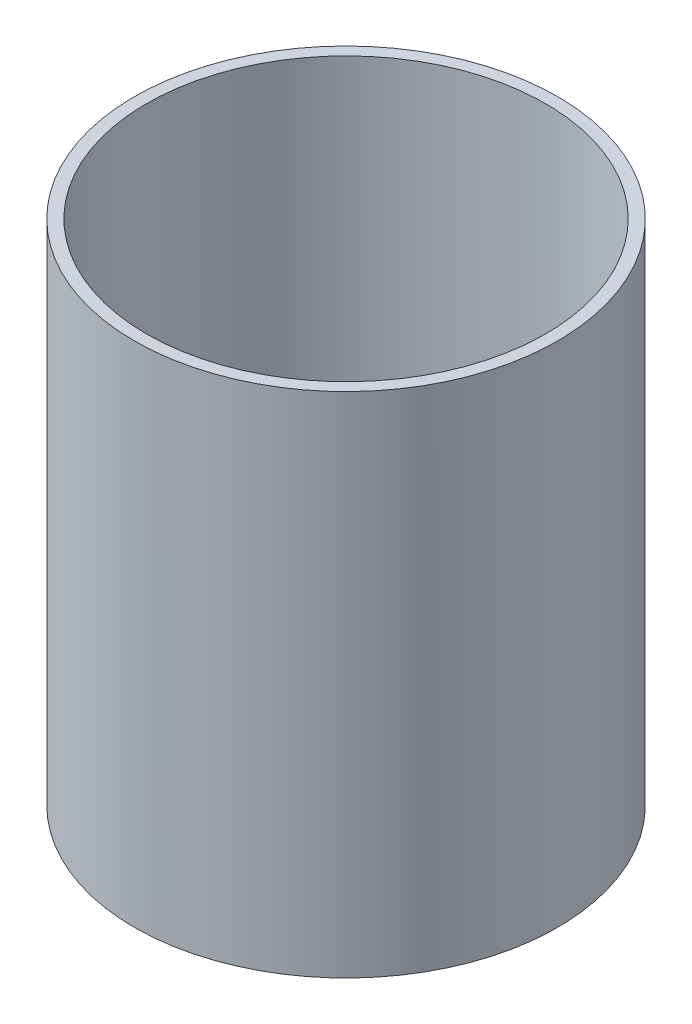
SolidWorks part; units mm, degrees
ref_plane "Front Plane" through (0, 0, 0) normal (0, 0, 1) x (1, 0, 0)
ref_plane "Top Plane" through (0, 0, 0) normal (0, 1, 0) x (1, 0, 0)
ref_plane "Right Plane" through (0, 0, 0) normal (1, 0, 0) x (0, 0, -1)
sketch "Sketch1" plane through (0, 0, 0) normal (0, 1, 0) x (1, 0, 0)
  circle A0 centre (0, 0) radius 17.78
  dimension "D1" = 35.56
extrude "Boss-Extrude1" add sketch "Sketch1" along normal blind 50.8 contours A0
sketch "Sketch2" plane through (0, 50.8, 0) normal (0, 1, 0) x (1, 0, 0)
  circle A0 centre (0, 0) radius 16.764
  dimension "D1" = 33.528
extrude "Cut-Extrude1" cut sketch "Sketch2" against normal blind 177.8
sketch "Sketch5" plane through (0, 0, 0) normal (0, 1, 0) x (1, 0, 0)
  line L0 (17.78, 2.54) -> (-17.78, 2.54)
  arc A1 (-17.78, 2.54) -> (17.78, 2.54) centre (0, 2.54) cw
extrude "Cut-Extrude3" cut sketch "Sketch5" along normal blind 8.128
sketch "Sketch6" plane through (0, 0, 0) normal (0, 1, 0) x (1, 0, 0)
  line L0 (17.78, -2.54) -> (-17.78, -2.54)
  arc A0 (-17.78, -2.54) -> (17.78, -2.54) centre (0, -1.0389) ccw
  point P2 (0, 0)
  point P3 (0, 0)
  point P4 (0, 0)
extrude "Cut-Extrude5" cut sketch "Sketch6" along normal blind 8.128
sketch "Sketch8" plane through (0, 0, 0) normal (0, 0, 1) x (1, 0, 0)
  line L0 (-17.5976, 8.128) -> (17.5976, 8.128) construction
  line L1 (16.1848, 8.128) -> (18.3495, 8.128)
  line L2 (16.1848, 8.128) -> (16.1848, 0)
  line L3 (16.1848, 0) -> (18.3495, 0)
  line L4 (18.3495, 8.128) -> (18.3495, 0)
extrude "Cut-Extrude6" cut sketch "Sketch8" along normal through all both and the other way through all
